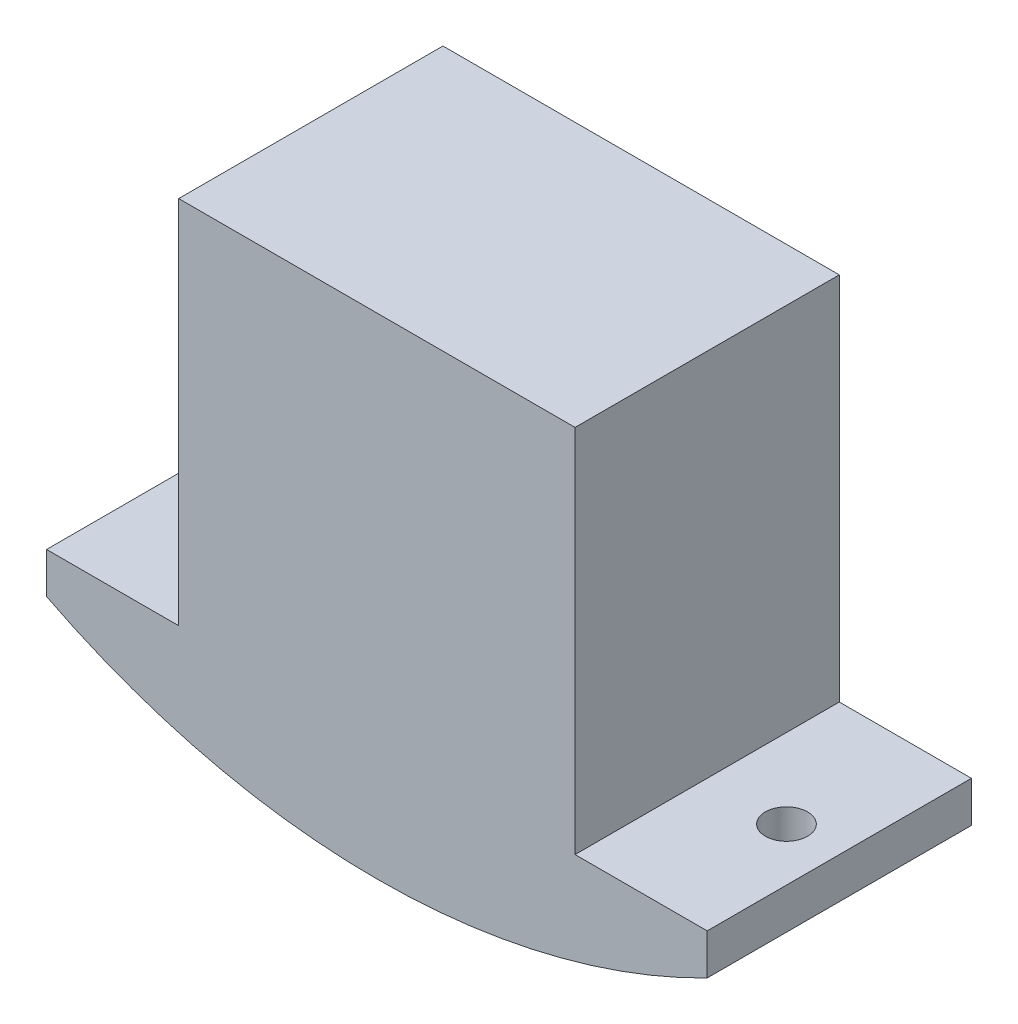
SolidWorks part; units mm, degrees
ref_plane "Plano frontal" through (0, 0, 0) normal (0, 0, 1) x (1, 0, 0)
ref_plane "Plano superior" through (0, 0, 0) normal (0, 1, 0) x (1, 0, 0)
ref_plane "Plano direito" through (0, 0, 0) normal (1, 0, 0) x (0, 0, -1)
sketch "Esboço1" plane through (0, 0, 0) normal (0, 0, 1) x (1, 0, 0)
  line L3 (-15, -45.8998) -> (-15, -17.8998)
  line L4 (-15, -17.8998) -> (15, -17.8998)
  line L5 (15, -17.8998) -> (15, -45.8998)
  line L9 (-25, -48.9898) -> (-25, -45.8998)
  line L10 (25, -48.9898) -> (25, -45.8998)
  line L11 (25, -45.8998) -> (15, -45.8998)
  line L12 (-25, -45.8998) -> (-15, -45.8998)
  arc A0 (-25, -48.9898) -> (25, -48.9898) centre (0, 0) ccw
  dimension "D1" = 110
  dimension "D2" = 10
  dimension "D3" = 50
  dimension "D4" = 10
  dimension "D5" = 28
  dimension "D6" = 3.09
  dimension "D7" = 3.09
  dimension "D8" = 28
extrude "Ressalto-extrusão2" add sketch "Esboço1" along normal blind 20
sketch "Esboço2" plane through (0, -45.8998, 0) normal (0, 1, 0) x (1, 0, 0)
  line L0 (-15, 0) -> (-25, 0) construction
  line L1 (25, 0) -> (15, 0) construction
  line L2 (-15, -20) -> (-15, 0) construction
  line L3 (15, -20) -> (15, 0) construction
  line L4 (25, -20) -> (25, 0) construction
  circle A0 centre (-21, -10) radius 1.6
  circle A1 centre (21, -10) radius 1.6
  dimension "D1" = 3.2
  dimension "D2" = 3.2
  dimension "D7" = 6
  dimension "D3" = 10
  dimension "D4" = 10
  dimension "D5" = 6
  dimension "D6" = 10
extrude "Corte-extrusão1" cut sketch "Esboço2" against normal blind 2.5
sketch "Esboço3" plane through (0, -48.3998, 0) normal (0, 1, 0) x (1, 0, 0)
  circle A0 centre (-21, -10) radius 3.1
  circle A1 centre (21, -10) radius 3.1
  dimension "D1" = 6.2
  dimension "D2" = 6.2
extrude "Corte-extrusão2" cut sketch "Esboço3" against normal up to next
